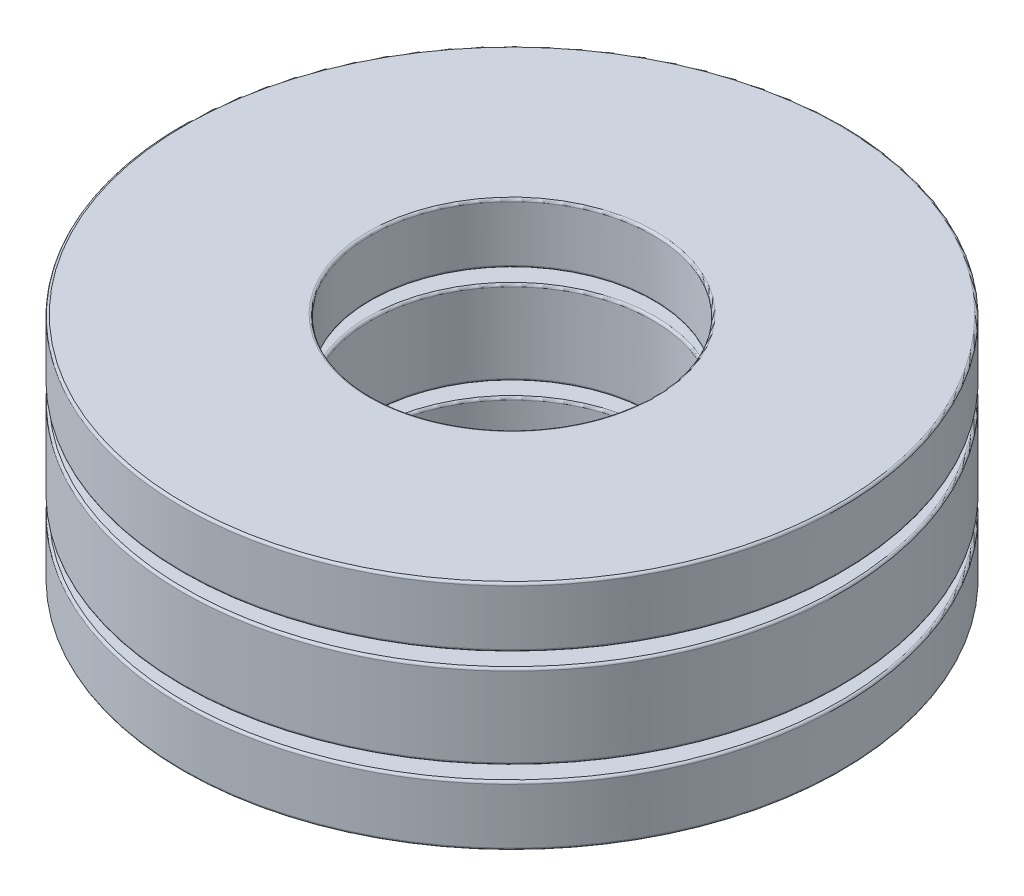
SolidWorks part; units mm, degrees
ref_plane "Front Plane" through (0, 0, 0) normal (0, 0, 1) x (1, 0, 0)
ref_plane "Top Plane" through (0, 0, 0) normal (0, 1, 0) x (1, 0, 0)
ref_plane "Right Plane" through (0, 0, 0) normal (1, 0, 0) x (0, 0, -1)
sketch "Sketch1" plane through (0, 0, 0) normal (0, 1, 0) x (1, 0, 0)
  circle A0 centre (0, 0) radius 7 construction
  circle A1 centre (0, 0) radius 3 construction
  circle A2 centre (0, 0) radius 5.15 construction
  dimension "B | OD" = 14
  dimension "A | ID" = 6
  dimension "C | Ball Circle" = 10.3
sketch "Sketch2" plane through (0, 0, 0) normal (0, 0, -1) x (-1, 0, 0)
  line L0 (-7, 2.46) -> (-7, 1.19) construction
  line L1 (-7, 0) -> (0, 0) construction
  line L3 (0, 2.46) -> (0, -2.46) construction
  line L4 (-7, 1.19) -> (-7, -1.19) construction
  line L6 (-7, -1.19) -> (-7, -2.46) construction
  point P11 (-7, 0)
  dimension "E | Thickness" = 4.92
  dimension "D | Washer Thickness" = 1.27
sketch "Sketch3" plane through (0, 0, 0) normal (0, 0, 1) x (1, 0, 0)
  line L2 (7, 0.8925) -> (3, 0.8925)
  line L4 (7, 0.8925) -> (7, -0.8925)
  line L7 (7, -0.8925) -> (3, -0.8925)
  line L8 (3, 0.8925) -> (3, -0.8925)
  line L11 (7, 1.19) -> (7, -1.19) construction
  point P8 (3, 0)
  dimension "D1" = 1.785
revolve "Revolve1" add sketch "Sketch3" angle 360 about L3
sketch "Sketch4" plane through (0, 0, 0) normal (0, 0, 1) x (1, 0, 0)
  line L0 (5.15, 1.19) -> (5.15, -1.19)
  arc A0 (5.15, 1.19) -> (5.15, -1.19) centre (5.15, 0) ccw
revolve "Cut-Revolve1" cut sketch "Sketch4" angle 360 about L0
sketch "Sketch5" plane through (0, 0, 0) normal (0, 0, 1) x (1, 0, 0)
  line L0 (5.15, 1.19) -> (5.15, -1.19)
  arc A0 (5.15, 1.19) -> (5.15, -1.19) centre (5.15, 0) ccw
revolve "Revolve2" add sketch "Sketch5" angle 360 about L0
pattern_circular "CirPattern1" count 8 every 45 about axis through (0, 2.46, 0) along (0, -1, 0) of bodies 187
pattern_circular "CirPattern2" count 8 every 45 about axis through (0, 0, 0) along (0, 1, 0) of "Cut-Revolve1"
sketch "Sketch6" plane through (0, 0, 0) normal (0, 0, 1) x (1, 0, 0)
  line L2 (7, 2.46) -> (3, 2.46)
  line L3 (7, 2.46) -> (7, 1.19)
  line L4 (7, 1.19) -> (3, 1.19)
  line L5 (3, 2.46) -> (3, 1.19)
  line L6 (7, -1.19) -> (3, -1.19)
  line L7 (7, -1.19) -> (7, -2.46)
  line L8 (7, -2.46) -> (3, -2.46)
  line L13 (3, -1.19) -> (3, -2.46)
  point P11 (3, 0)
revolve "Revolve3" add sketch "Sketch6" angle 360 about L3
fillet "Fillet1" radius 0.0492 4 edges at (0, 1.19, 3) (0, 1.19, 7) (0, 2.46, 7) (0, 2.46, 3)
fillet "Fillet2" radius 0.0492 20 edges at (0, -0.8925, 3) (0, -0.8925, 7) (5.15, -0.8925, 0.7871) (3.085, -0.8925, 4.1982) (-0.7871, -0.8925, 5.15) (-4.1982, -0.8925, 3.085) (-5.15, -0.8925, -0.7871) (-3.085, -0.8925, -4.1982) (0.7871, -0.8925, -5.15) (0, 0.8925, 7) (0, 0.8925, 3) (5.15, 0.8925, -0.7871) (4.1982, 0.8925, 3.085) (0.7871, 0.8925, 5.15) (-3.085, 0.8925, 4.1982) (-5.15, 0.8925, 0.7871) (-4.1982, 0.8925, -3.085) (-0.7871, 0.8925, -5.15) (4.1982, -0.8925, -3.085) (3.085, 0.8925, -4.1982)
fillet "Fillet3" radius 0.0492 4 edges at (0, -1.19, 7) (0, -1.19, 3) (0, -2.46, 3) (0, -2.46, 7)
equation "\"Angle@CirPattern1\" = 360/\"Balls@CirPattern1\""
equation "\"D1@CirPattern2\" = \"Balls@CirPattern1\""
equation "\"D2@CirPattern2\" = \"Angle@CirPattern1\""
equation "\"D1@Sketch3\"=(\"E | Thickness@Sketch2\"-(2*\"D | Washer Thickness@Sketch2\"))*.75"
equation "\"D1@Fillet1\"=\"E | Thickness@Sketch2\" * .01"
equation "\"D1@Fillet2\"=\"D1@Fillet1\""
equation "\"D1@Fillet3\"=\"D1@Fillet1\""
